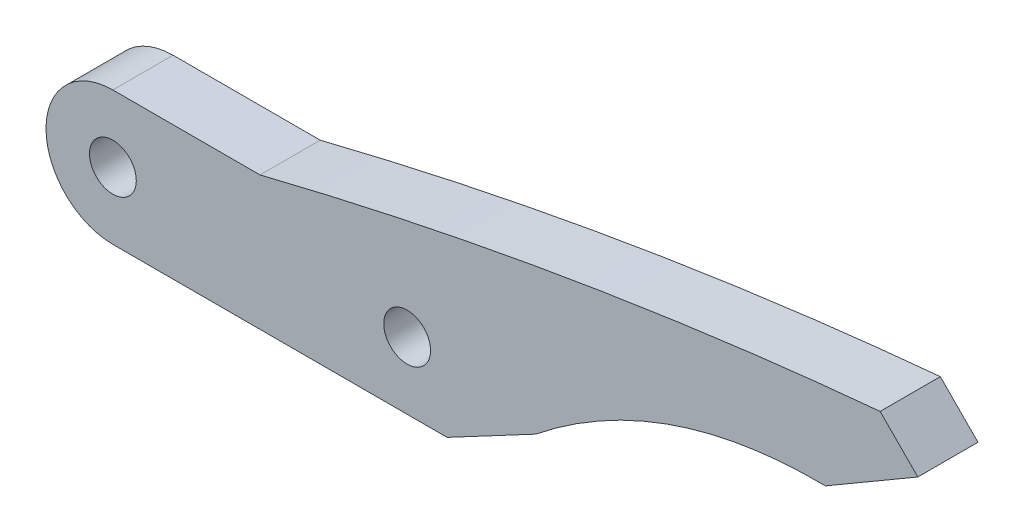
SolidWorks part; units mm, degrees
ref_plane "Front Plane" through (0, 0, 0) normal (0, 0, 1) x (1, 0, 0)
ref_plane "Top Plane" through (0, 0, 0) normal (0, 1, 0) x (1, 0, 0)
ref_plane "Right Plane" through (0, 0, 0) normal (1, 0, 0) x (0, 0, -1)
sketch "Sketch1" plane through (0, 0, 0) normal (0, 0, 1) x (1, 0, 0)
  line L0 (-11, 0) -> (11, 0) construction
  line L1 (0, 0) -> (0, 6.875) construction
  line L3 (-16, -5) -> (16, -5)
  line L4 (-16, -5) -> (-16, 5)
  line L5 (-16, 5) -> (16, 5)
  line L6 (16, -5) -> (16, 5)
  line L7 (-16, -5) -> (16, 5) construction
  line L8 (-16, 5) -> (16, -5) construction
  circle A0 centre (-11, 0) radius 1.75
  circle A1 centre (-11, 0) radius 5
  circle A2 centre (11, 0) radius 1.75
  circle A3 centre (11, 0) radius 5
  point P4 (0, 0)
  dimension "D2" = 3.5
  dimension "D3" = 10
  dimension "D1" = 22
extrude "Boss-Extrude1" add sketch "Sketch1" along normal blind 4.5 contours A1 A0 | A3 A2 | L3 A3 L5 A1
sketch "Sketch2" plane through (0, 0, 4.5) normal (0, 0, 1) x (1, 0, 0)
  line L0 (46.364, 12.87) -> (49.1808, 10.03)
  line L1 (49.1808, 10.03) -> (42.27, 6)
  line L2 (-11, -5) -> (11, -5) construction
  line L3 (11, 0) -> (11, -5) construction
  line L4 (20.61, -1.48) -> (13.99, -5)
  line L5 (13.99, -5) -> (11, -5)
  line L6 (-11, 5) -> (11, 5) construction
  line L7 (0, 5) -> (11, 5)
  arc A0 (11, -5) -> (11, 5) centre (11, 0) ccw construction
  arc A1 (11, -5) -> (11, 5) centre (11, 0) ccw
  spline S0 degree 2 poles (42.27, 6) (30.1462, 6.1573) (20.61, -1.48) knots 0 0 0 1 1 1
  spline S1 degree 2 poles (0, 5) (22.8855, 10.7079) (46.364, 12.87) knots 0 0 0 1 1 1
  arc M9 (11, -5) -> (11, 5) centre (11, 0) ccw
  line M10 (11, 5) -> (-11, 5)
  dimension "D1" = 4
  dimension "D2" = 8
  dimension "D3" = 17.87
  dimension "D4" = 15.03
  dimension "D5" = 11
  dimension "D6" = 9.45
  dimension "D7" = 3.52
  dimension "D8" = 9.61
  dimension "D9" = 20.52
  dimension "D10" = 31.27
  dimension "D11" = 2.99
  dimension "D12" = 13.52
  dimension "D13" = 15.07
extrude "Boss-Extrude2" add sketch "Sketch2" against normal up to surface (4.5 mm away) contours S1 L5 L4 S0 L1 L0 M10 M9 up to face at (-9.25, 0, 0)
